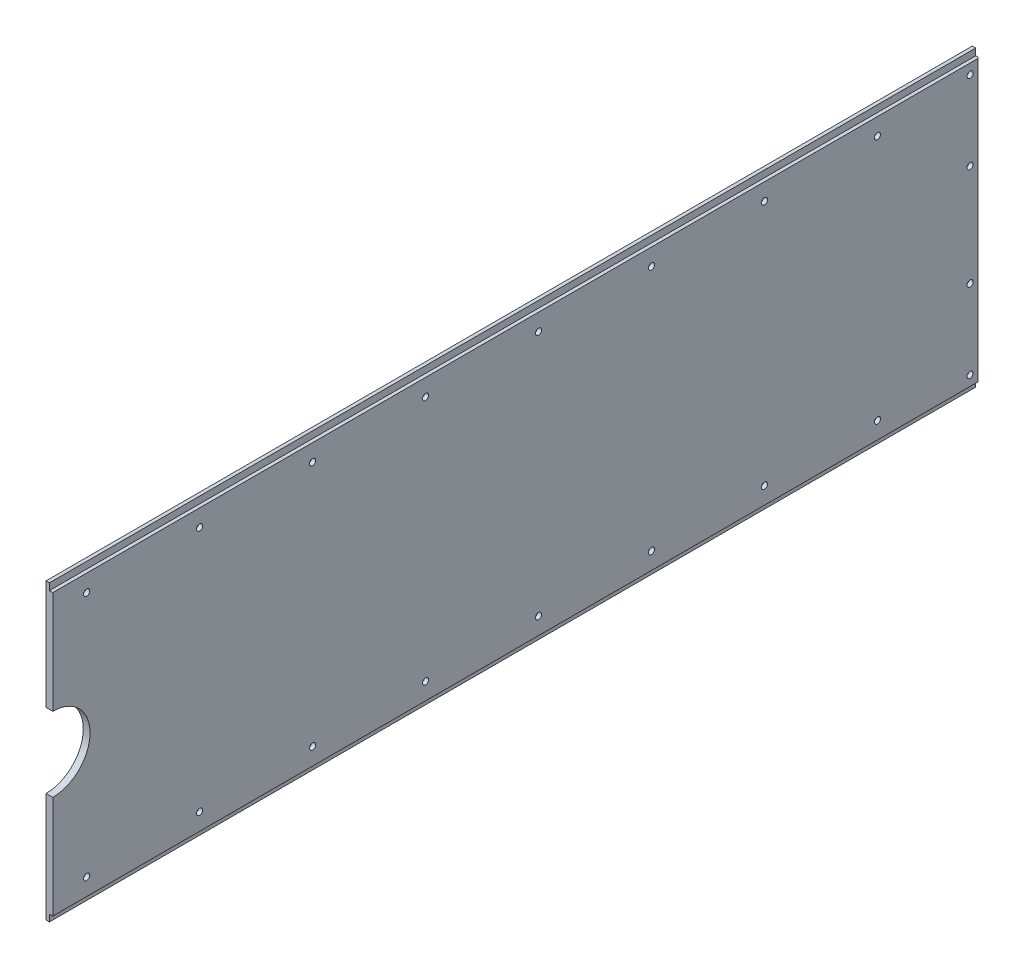
SolidWorks part; units mm, degrees
material "1060 Legierung"
ref_plane "Front Plane" through (0, 0, 0) normal (0, 0, 1) x (1, 0, 0)
ref_plane "Top Plane" through (0, 0, 0) normal (0, 1, 0) x (1, 0, 0)
ref_plane "Right Plane" through (0, 0, 0) normal (1, 0, 0) x (0, 0, -1)
sketch "Sketch1" plane through (0, 0, 0) normal (1, 0, 0) x (0, 0, -1)
  line L0 (0, 0) -> (59.3183, 0) construction
  line L1 (0, 28.1909) -> (0, -28.8956) construction
  line L2 (-410, 130) -> (410, 130)
  line L3 (410, 130) -> (410, -130)
  line L4 (410, -130) -> (-410, -130)
  line L5 (-410, -130) -> (-410, -33)
  line L6 (-410, 33) -> (-410, 130)
  arc A0 (-410, -33) -> (-410, 33) centre (-410, 0) ccw
  dimension "D3" = 33
  dimension "D1" = 260
  dimension "D2" = 820
extrude "Boss-Extrude1" add sketch "Sketch1" along normal blind 6
sketch "Skizze1" plane through (0, 0, 410) normal (0, 0, 1) x (1, 0, 0)
  line L0 (-10.5918, 0) -> (26.1347, 0) construction
  line L1 (3, -130) -> (3, -124)
  line L2 (6, 130) -> (3, 130)
  line L3 (6, 130) -> (6, 124)
  line L4 (6, 124) -> (3, 124)
  line L5 (3, 130) -> (3, 124)
  line L6 (6, -124) -> (3, -124)
  line L7 (6, -130) -> (6, -124)
  line L8 (6, -130) -> (3, -130)
  dimension "D1" = 6
  dimension "D2" = 3
extrude "Schnitt-Linear austragen1" cut sketch "Skizze1" against normal through all
hole_wizard "Formsenkung fur M5 Linsensenkschraube mit Schlitz1" positions "Skizze3" profile "Skizze2" countersink size "M5" standard "Din" end condition through all
sketch "Skizze3" plane through (0, 0, 0) normal (-1, 0, 0) x (0, 0, 1)
  line L0 (-456.453, 0) -> (41.6709, 0) construction
  line L2 (-410, -130) -> (-410, 130) construction
  point P0 (-402, -115)
  point P2 (-402, -45)
  dimension "D1" = 45
  dimension "D2" = 115
  dimension "D3" = 8
  dimension "D4" = 8
sketch "Skizze2" plane through (0, -115, -402) normal (0, 1, 0) x (0, 0, 1)
  line L0 (0, 0) -> (0, 6)
  line L1 (0, 6) -> (2.75, 6)
  line L2 (2.75, 6) -> (2.75, 2.45)
  line L3 (2.75, 2.45) -> (5.2, 0)
  line L5 (5.2, 0) -> (0, 0)
  line L6 (-2.75, 2.45) -> (-5.2, 0) construction
  line L11 (0, -6.35) -> (0, 107.95) construction
  dimension "Bohrerdurchmesser" = 5.5
  dimension "Bohrungstiefe" = 6
  dimension "Senkdurchmesser (Oben)" = 10.4
  dimension "Senkwinkel (Oben)" = 90
chamfer "Chamfer1" distance 1 angle 45 1 edges at (6, 0, -410)
hole_wizard "CSK for M5 Countersunk Raised Head Screw1" positions "Sketch3" profile "Sketch2" countersink size "M5" standard "DIN" end condition through all
sketch "Sketch3" plane through (0, 0, 0) normal (-1, 0, 0) x (0, 0, 1)
  line L0 (-410, 130) -> (410, 130) construction
  line L1 (-410, -130) -> (-410, 130) construction
  point P0 (-320, 109)
  dimension "D1" = 21
  dimension "D2" = 90
sketch "Sketch2" plane through (0, 109, -320) normal (0, 1, 0) x (0, 0, 1)
  line L0 (0, 0) -> (0, 6)
  line L1 (0, 6) -> (2.75, 6)
  line L2 (2.75, 6) -> (2.75, 2.45)
  line L3 (2.75, 2.45) -> (5.2, 0)
  line L5 (5.2, 0) -> (0, 0)
  line L6 (-2.75, 2.45) -> (-5.2, 0) construction
  line L11 (0, -6.35) -> (0, 107.95) construction
  dimension "Thru Hole Dia." = 5.5
  dimension "Thru Hole Depth" = 6
  dimension "Near C'Sink Dia." = 10.4
  dimension "Near C'Sink Angle" = 90
pattern_linear "LPattern1" count 8 spacing 100 along (0, 0, 1) of "CSK for M5 Countersunk Raised Head Screw1"
mirror "Spiegeln1" about plane through (0, 0, 0) normal (0, 1, 0) of "LPattern1", "Formsenkung fur M5 Linsensenkschraube mit Schlitz1", "CSK for M5 Countersunk Raised Head Screw1"
